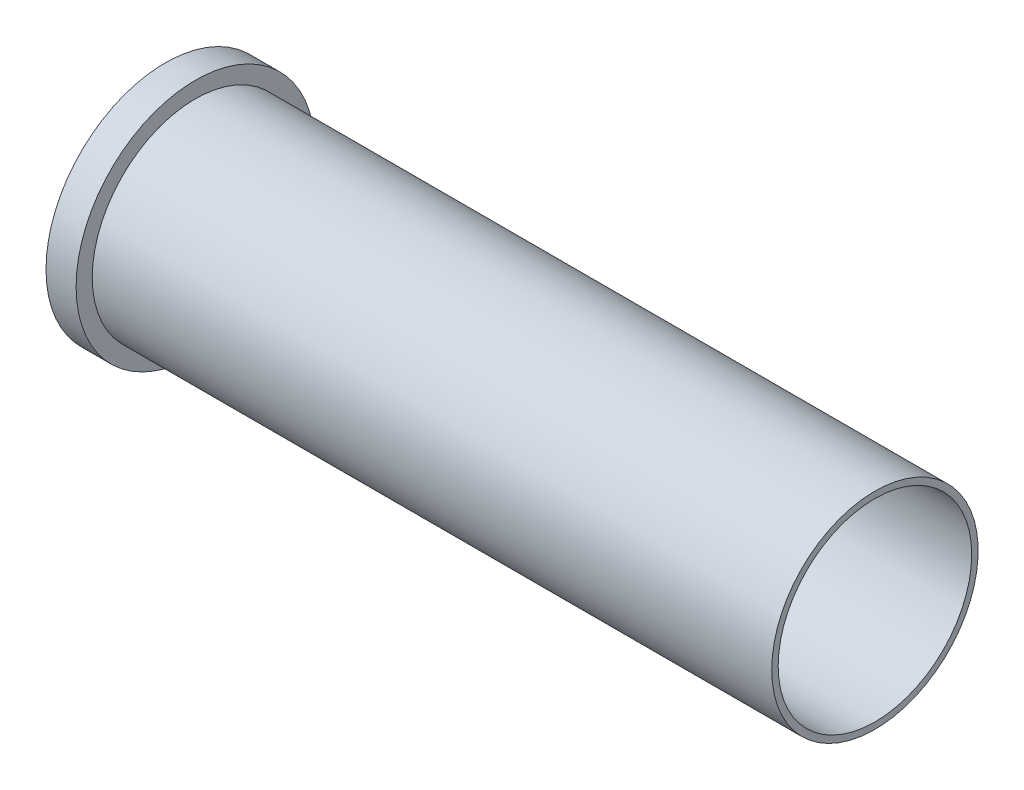
SolidWorks part; units mm, degrees
ref_plane "Plano frontal" through (0, 0, 0) normal (0, 0, 1) x (1, 0, 0)
ref_plane "Plano superior" through (0, 0, 0) normal (0, 1, 0) x (1, 0, 0)
ref_plane "Plano direito" through (0, 0, 0) normal (1, 0, 0) x (0, 0, -1)
sketch "Esboço1" plane through (0, 0, 0) normal (0, 1, 0) x (1, 0, 0)
  line L0 (0, 0) -> (31.5077, 0) construction
  line L1 (3.8, 1.05) -> (2.9604, 1.05)
  line L2 (2.9604, 1.05) -> (2.9604, 2.25)
  line L3 (2.9604, 2.25) -> (0, 2.25)
  line L4 (0, 2.25) -> (0, 5.55)
  line L5 (0, 5.55) -> (1.4, 5.55)
  line L6 (1.4, 5.55) -> (1.4, 4.8)
  line L7 (1.4, 4.8) -> (33, 4.8)
  line L8 (33, 4.8) -> (33, 4.5)
  line L9 (33, 4.5) -> (3.8, 4.5)
  line L10 (3.8, 4.5) -> (3.8, 1.05)
  point P3 (0, 1.0397)
  point P4 (31.5077, 1.0397)
  point P5 (3.7627, 0)
  point P8 (3.7627, 9.568)
  point P11 (3.8, 1.05)
  point P12 (3.7627, 1.0397)
  point P23 (33, 4.65)
  dimension "D1" = 3.3
  dimension "D2" = 5.55
  dimension "D3" = 1.2
  dimension "D4" = 3.45
  dimension "D5" = 3.8
  dimension "D6" = 1.4
  dimension "D7" = 33
  dimension "D8" = 0.3
  dimension "D9" = 0.75
revolve "Revolução1" add sketch "Esboço1" angle 360 about L0
